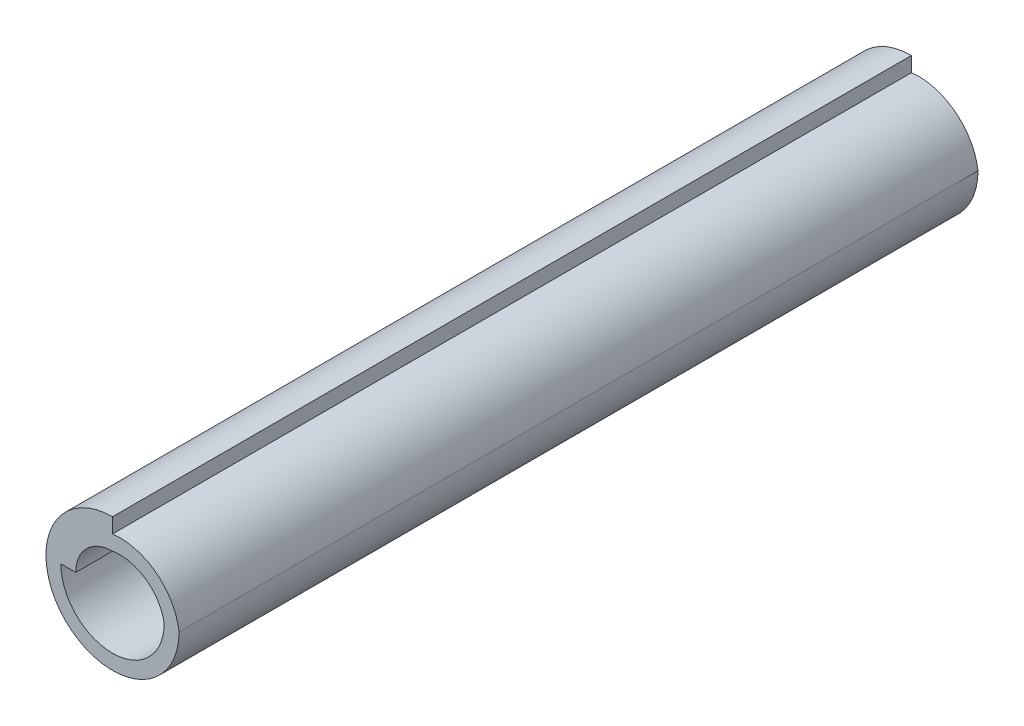
SolidWorks part; units mm, degrees
ref_plane "Plane1" through (0, 0, 0) normal (0, 0, 1) x (1, 0, 0)
ref_plane "Plane2" through (0, 0, 0) normal (0, 1, 0) x (1, 0, 0)
ref_plane "Plane3" through (0, 0, 0) normal (1, 0, 0) x (0, 0, -1)
sketch "Sketch1" plane through (0, 0, 0) normal (0, 0, 1) x (1, 0, 0)
  line L0 (0, 1.94) -> (0, 2.5)
  line L1 (-1.94, 0) -> (-1.38, 0)
  line L2 (0, 1.38) -> (1.94, 0) construction
  line L3 (0.28, -0.28) -> (0.97, 0.69) construction
  line L4 (0, 1.94) -> (2.5, 0) construction
  line L5 (0.28, -0.28) -> (1.25, 0.97) construction
  arc A0 (0, 2.5) -> (2.5, 0) centre (0, 0) ccw
  arc A1 (-1.94, 0) -> (1.94, 0) centre (0, 0) ccw
  arc A2 (0, 1.38) -> (-1.38, 0) centre (0, 0) ccw
  arc A3 (1.94, 0) -> (0, 1.38) centre (0.28, -0.28) ccw
  arc A4 (2.5, 0) -> (0, 1.94) centre (0.28, -0.28) ccw
  dimension "Diameter" = 5
  dimension "D2" = 3.88
  dimension "Thickness" = 0.56
  dimension "D1" = 0.56
extrude "Base-Extrude" add sketch "Sketch1" along normal mid plane 30
equation "\"D1@Sketch1\" = \"Thickness@Sketch1\""
equation "\"D2@Sketch1\" = \"Diameter@Sketch1\" - \"Thickness@Sketch1\" * 2"
